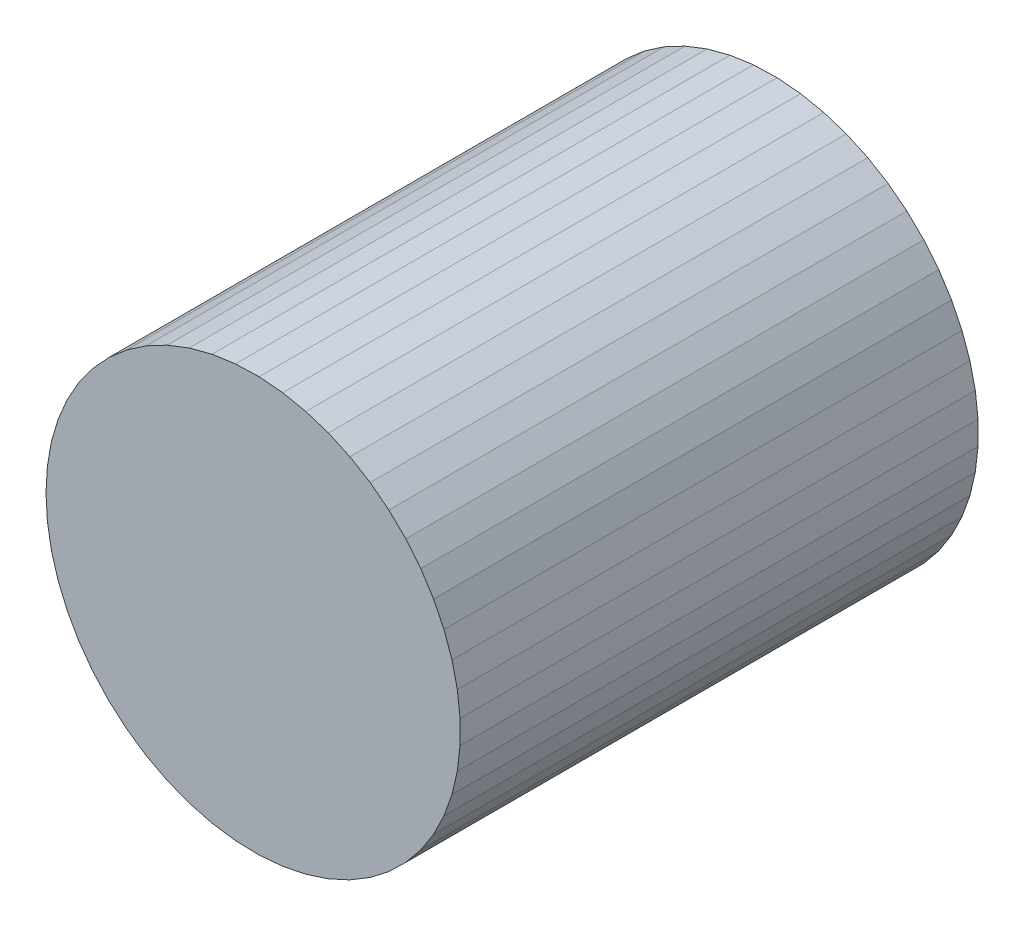
SolidWorks part; units mm, degrees
ref_plane "Front Plane" through (0, 0, 0) normal (0, 0, 1) x (1, 0, 0)
ref_plane "Top Plane" through (0, 0, 0) normal (0, 1, 0) x (1, 0, 0)
ref_plane "Right Plane" through (0, 0, 0) normal (1, 0, 0) x (0, 0, -1)
sketch "Biên dạng ngoài theo phôi gốc" plane through (0, 0, 0) normal (0, 0, 1) x (1, 0, 0)
  line L0 (-20, 0) -> (-19.8696, -2.2798)
  line L1 (-19.8696, -2.2798) -> (-19.4802, -4.5299)
  line L2 (-19.4802, -4.5299) -> (-18.8369, -6.721)
  line L3 (-18.8369, -6.721) -> (-17.948, -8.8244)
  line L4 (-17.948, -8.8244) -> (-16.8251, -10.8128)
  line L5 (-16.8251, -10.8128) -> (-15.4828, -12.6602)
  line L6 (-15.4828, -12.6602) -> (-13.9388, -14.3426)
  line L7 (-13.9388, -14.3426) -> (-12.213, -15.838)
  line L8 (-12.213, -15.838) -> (-10.3279, -17.127)
  line L9 (-10.3279, -17.127) -> (-8.3083, -18.1926)
  line L10 (-8.3083, -18.1926) -> (-6.1803, -19.0211)
  line L11 (-6.1803, -19.0211) -> (-3.9718, -19.6017)
  line L12 (-3.9718, -19.6017) -> (-1.7115, -19.9266)
  line L13 (-1.7115, -19.9266) -> (0.5711, -19.9918)
  line L14 (0.5711, -19.9918) -> (2.8463, -19.7964)
  line L15 (2.8463, -19.7964) -> (5.0844, -19.3429)
  line L16 (5.0844, -19.3429) -> (7.2562, -18.6373)
  line L17 (7.2562, -18.6373) -> (9.3333, -17.6887)
  line L18 (9.3333, -17.6887) -> (11.2889, -16.5094)
  line L19 (11.2889, -16.5094) -> (13.0972, -15.115)
  line L20 (13.0972, -15.115) -> (14.7348, -13.5235)
  line L21 (14.7348, -13.5235) -> (16.1803, -11.7557)
  line L22 (16.1803, -11.7557) -> (17.4149, -9.8347)
  line L23 (17.4149, -9.8347) -> (18.4225, -7.7854)
  line L24 (18.4225, -7.7854) -> (19.1899, -5.6347)
  line L25 (19.1899, -5.6347) -> (19.7071, -3.4104)
  line L26 (19.7071, -3.4104) -> (19.9674, -1.1418)
  line L27 (19.9674, -1.1418) -> (19.9674, 1.1418)
  line L28 (19.9674, 1.1418) -> (19.7071, 3.4104)
  line L29 (19.7071, 3.4104) -> (19.1899, 5.6347)
  line L30 (19.1899, 5.6347) -> (18.4225, 7.7854)
  line L31 (18.4225, 7.7854) -> (17.4149, 9.8347)
  line L32 (17.4149, 9.8347) -> (16.1803, 11.7557)
  line L33 (16.1803, 11.7557) -> (14.7348, 13.5235)
  line L34 (14.7348, 13.5235) -> (13.0972, 15.115)
  line L35 (13.0972, 15.115) -> (11.2889, 16.5094)
  line L36 (11.2889, 16.5094) -> (9.3333, 17.6887)
  line L37 (9.3333, 17.6887) -> (7.2562, 18.6373)
  line L38 (7.2562, 18.6373) -> (5.0844, 19.3429)
  line L39 (5.0844, 19.3429) -> (2.8463, 19.7964)
  line L40 (2.8463, 19.7964) -> (0.5711, 19.9918)
  line L41 (0.5711, 19.9918) -> (-1.7115, 19.9266)
  line L42 (-1.7115, 19.9266) -> (-3.9718, 19.6017)
  line L43 (-3.9718, 19.6017) -> (-6.1803, 19.0211)
  line L44 (-6.1803, 19.0211) -> (-8.3083, 18.1926)
  line L45 (-8.3083, 18.1926) -> (-10.3279, 17.127)
  line L46 (-10.3279, 17.127) -> (-12.213, 15.838)
  line L47 (-12.213, 15.838) -> (-13.9388, 14.3426)
  line L48 (-13.9388, 14.3426) -> (-15.4828, 12.6602)
  line L49 (-15.4828, 12.6602) -> (-16.8251, 10.8128)
  line L50 (-16.8251, 10.8128) -> (-17.948, 8.8244)
  line L51 (-17.948, 8.8244) -> (-18.8369, 6.721)
  line L52 (-18.8369, 6.721) -> (-19.4802, 4.5299)
  line L53 (-19.4802, 4.5299) -> (-19.8696, 2.2798)
  line L54 (-19.8696, 2.2798) -> (-20, 0)
extrude "Thân ngoài" add sketch "Biên dạng ngoài theo phôi gốc" along normal blind 50
sketch "Biên dạng trong cách thành ngoài 0,3 mm" plane through (0, 0, 0) normal (0, 0, 1) x (1, 0, 0)
  line L0 (-19.5711, -2.2456) -> (-19.1876, -4.4619)
  line L1 (-19.1876, -4.4619) -> (-18.5539, -6.62)
  line L2 (-18.5539, -6.62) -> (-17.6783, -8.6918)
  line L3 (-17.6783, -8.6918) -> (-16.5723, -10.6504)
  line L4 (-16.5723, -10.6504) -> (-15.2502, -12.47)
  line L5 (-15.2502, -12.47) -> (-13.7293, -14.1271)
  line L6 (-13.7293, -14.1271) -> (-12.0295, -15.6001)
  line L7 (-12.0295, -15.6001) -> (-10.1728, -16.8697)
  line L8 (-10.1728, -16.8697) -> (-8.1835, -17.9193)
  line L9 (-8.1835, -17.9193) -> (-6.0875, -18.7353)
  line L10 (-6.0875, -18.7353) -> (-3.9121, -19.3071)
  line L11 (-3.9121, -19.3071) -> (-1.6858, -19.6272)
  line L12 (-1.6858, -19.6272) -> (0.5625, -19.6915)
  line L13 (0.5625, -19.6915) -> (2.8035, -19.499)
  line L14 (2.8035, -19.499) -> (5.008, -19.0523)
  line L15 (5.008, -19.0523) -> (7.1471, -18.3573)
  line L16 (7.1471, -18.3573) -> (9.1931, -17.4229)
  line L17 (9.1931, -17.4229) -> (11.1193, -16.2614)
  line L18 (11.1193, -16.2614) -> (12.9004, -14.8879)
  line L19 (12.9004, -14.8879) -> (14.5134, -13.3203)
  line L20 (14.5134, -13.3203) -> (15.9372, -11.5791)
  line L21 (15.9372, -11.5791) -> (17.1533, -9.6869)
  line L22 (17.1533, -9.6869) -> (18.1457, -7.6684)
  line L23 (18.1457, -7.6684) -> (18.9015, -5.55)
  line L24 (18.9015, -5.55) -> (19.411, -3.3592)
  line L25 (19.411, -3.3592) -> (19.6674, -1.1246)
  line L26 (19.6674, -1.1246) -> (19.6674, 1.1246)
  line L27 (19.6674, 1.1246) -> (19.411, 3.3592)
  line L28 (19.411, 3.3592) -> (18.9015, 5.55)
  line L29 (18.9015, 5.55) -> (18.1457, 7.6684)
  line L30 (18.1457, 7.6684) -> (17.1533, 9.6869)
  line L31 (17.1533, 9.6869) -> (15.9372, 11.5791)
  line L32 (15.9372, 11.5791) -> (14.5134, 13.3203)
  line L33 (14.5134, 13.3203) -> (12.9004, 14.8879)
  line L34 (12.9004, 14.8879) -> (11.1193, 16.2614)
  line L35 (11.1193, 16.2614) -> (9.1931, 17.4229)
  line L36 (9.1931, 17.4229) -> (7.1471, 18.3573)
  line L37 (7.1471, 18.3573) -> (5.008, 19.0523)
  line L38 (5.008, 19.0523) -> (2.8035, 19.499)
  line L39 (2.8035, 19.499) -> (0.5625, 19.6915)
  line L40 (0.5625, 19.6915) -> (-1.6858, 19.6272)
  line L41 (-1.6858, 19.6272) -> (-3.9121, 19.3071)
  line L42 (-3.9121, 19.3071) -> (-6.0875, 18.7353)
  line L43 (-6.0875, 18.7353) -> (-8.1835, 17.9193)
  line L44 (-8.1835, 17.9193) -> (-10.1728, 16.8697)
  line L45 (-10.1728, 16.8697) -> (-12.0295, 15.6001)
  line L46 (-12.0295, 15.6001) -> (-13.7293, 14.1271)
  line L47 (-13.7293, 14.1271) -> (-15.2502, 12.47)
  line L48 (-15.2502, 12.47) -> (-16.5723, 10.6504)
  line L49 (-16.5723, 10.6504) -> (-17.6783, 8.6918)
  line L50 (-17.6783, 8.6918) -> (-18.5539, 6.62)
  line L51 (-18.5539, 6.62) -> (-19.1876, 4.4619)
  line L52 (-19.1876, 4.4619) -> (-19.5711, 2.2456)
  line L53 (-19.5711, 2.2456) -> (-19.6995, 0)
  line L54 (-19.6995, 0) -> (-19.5711, -2.2456)
extrude "Khoang rỗng kín" cut sketch "Biên dạng trong cách thành ngoài 0,3 mm" along normal blind 49 from offset 0.5
